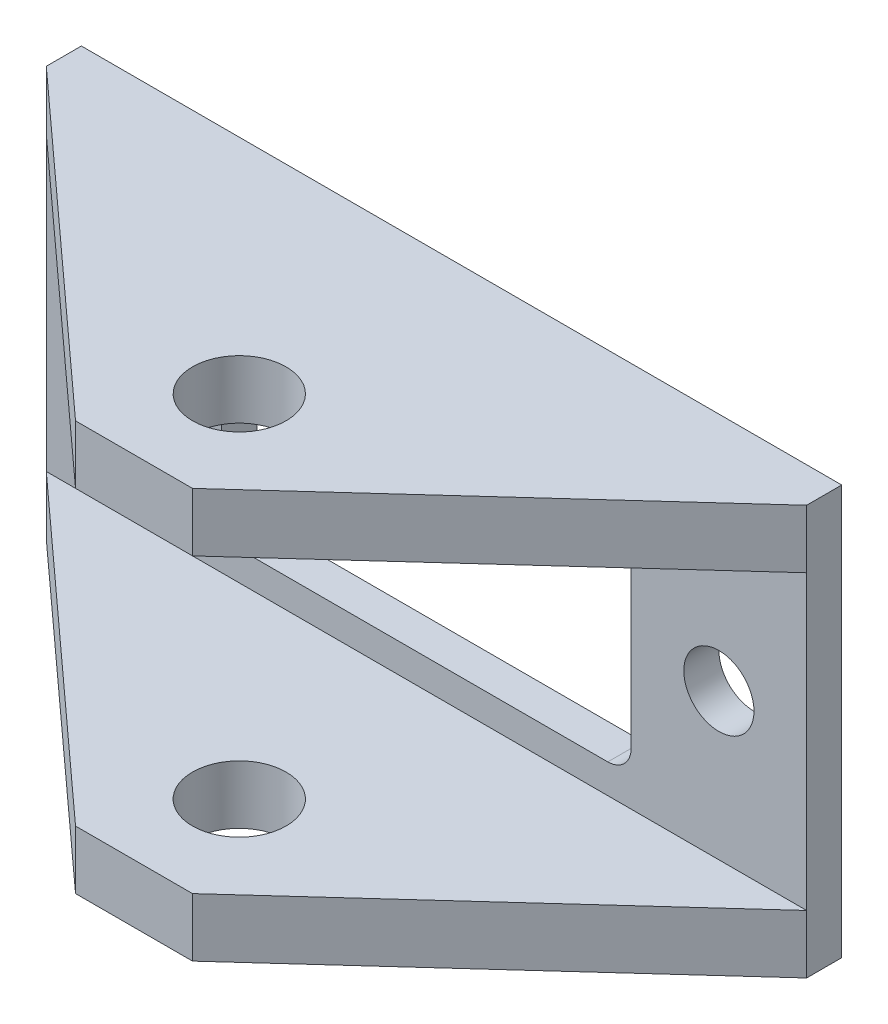
SolidWorks part; units mm, degrees
material "7075-T6 (SN)"
ref_plane "Front Plane" through (0, 0, 0) normal (0, 0, 1) x (1, 0, 0)
ref_plane "Top Plane" through (0, 0, 0) normal (0, 1, 0) x (1, 0, 0)
ref_plane "Right Plane" through (0, 0, 0) normal (1, 0, 0) x (0, 0, -1)
sketch "Sketch1" plane through (0, 0, 0) normal (0, 1, 0) x (1, 0, 0)
  line L0 (0, 0) -> (0, -15.5)
  line L1 (-32.5, 12.5) -> (32.5, 12.5)
  line L5 (-32.5, 12.5) -> (0, 0) construction
  line L6 (0, 0) -> (32.5, 12.5) construction
  line L7 (-5, -15.5) -> (5, -15.5)
  line L8 (-32.5, 12.5) -> (-32.5, 9.5)
  line L9 (32.5, 12.5) -> (32.5, 9.5)
  line L10 (-32.5, 9.5) -> (-5, -15.5)
  line L11 (5, -15.5) -> (32.5, 9.5)
  point P0 (0, 0)
  point P10 (0, -15.5)
  dimension "D1" = 28
  dimension "D2" = 65
  dimension "D3" = 10
extrude "Boss-Extrude1" add sketch "Sketch1" along normal blind 35
sketch "Sketch4" plane through (0, 0, 0) normal (0, 0, 1) x (1, 0, 0)
  line L0 (32.5, 0) -> (-32.5, 35)
  line L1 (32.5, 35) -> (32.5, 0) construction
  line L2 (-32.5, 30) -> (32.5, 30)
  line L3 (-32.5, 30) -> (-32.5, 5)
  line L4 (-32.5, 5) -> (32.5, 5)
  line L5 (32.5, 30) -> (32.5, 5)
  line L6 (-32.5, 30) -> (32.5, 5) construction
  line L7 (-32.5, 5) -> (32.5, 30) construction
  point P4 (0, 17.5)
  dimension "D1" = 25
extrude "Cut-Extrude1" cut sketch "Sketch4" against normal up to vertex (9.5 mm away) and the other way up to surface (15.5 mm away) contours L5 L2 L0 L4 | L3 L4 L0 L2 other way up to face at (0, 17.5, 15.5)
sketch "Sketch5" plane through (0, 0, 0) normal (0, 0, 1) x (1, 0, 0)
  line L0 (-32.5, 30) -> (32.5, 5)
  line L1 (-25, 17.5) -> (25, 17.5)
  line L2 (-17.5, 27.5) -> (17.5, 27.5)
  line L3 (-17.5, 27.5) -> (-17.5, 7.5)
  line L4 (-17.5, 7.5) -> (17.5, 7.5)
  line L5 (17.5, 27.5) -> (17.5, 7.5)
  line L6 (-17.5, 27.5) -> (17.5, 7.5) construction
  line L7 (-17.5, 7.5) -> (17.5, 27.5) construction
  circle A0 centre (-25, 17.5) radius 3
  circle A1 centre (25, 17.5) radius 3
  point P4 (0, 17.5)
  point P12 (0, 17.5)
  dimension "D1" = 20
  dimension "D2" = 35
extrude "Cut-Extrude2" cut sketch "Sketch5" against normal through all both and the other way through all
ref_plane "Plane2" through (0, 35, 0) normal (0, 1, 0) x (1, 0, 0)
sketch "Sketch6" plane through (0, 35, 0) normal (0, 1, 0) x (1, 0, 0)
  line L0 (0, 12.5) -> (0, -6.5)
  line L3 (-32.5, 12.5) -> (32.5, 12.5) construction
  circle A2 centre (0, -6.5) radius 4
extrude "Cut-Extrude3" cut sketch "Sketch6" against normal through all both and the other way through all
fillet "Fillet1" radius 2 4 edges at (-17.5, 7.5, -11) (17.5, 7.5, -11) (17.5, 27.5, -11) (-17.5, 27.5, -11)
